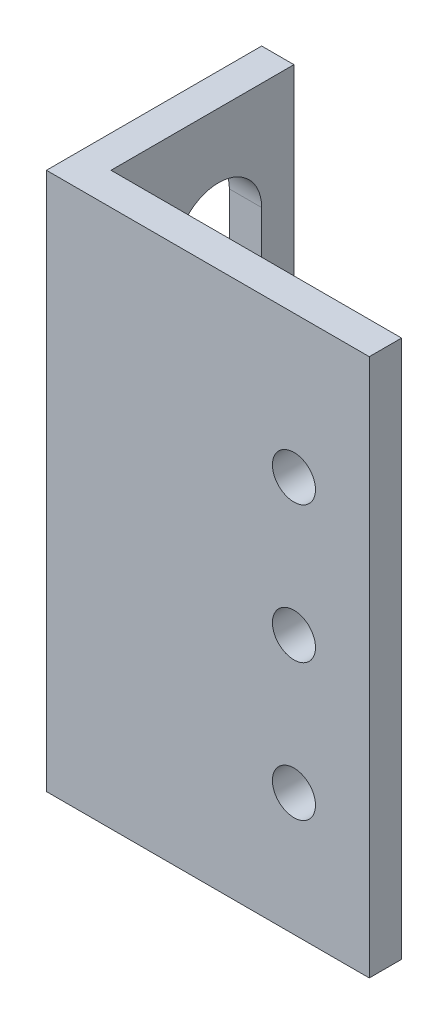
SolidWorks part; units mm, degrees
ref_plane "前视基准面" through (0, 0, 0) normal (0, 0, 1) x (1, 0, 0)
ref_plane "上视基准面" through (0, 0, 0) normal (0, 1, 0) x (1, 0, 0)
ref_plane "右视基准面" through (0, 0, 0) normal (1, 0, 0) x (0, 0, -1)
sketch "草图1" plane through (0, 0, 0) normal (0, 1, 0) x (1, 0, 0)
  line L2 (-1.5, 10) -> (1.5, 10)
  line L3 (-1.5, 10) -> (-1.5, -10)
  line L4 (-1.5, -10) -> (1.5, -10)
  line L5 (1.5, 10) -> (1.5, -10)
  line L6 (-1.5, 10) -> (1.5, -10) construction
  line L7 (-1.5, -10) -> (1.5, 10) construction
  line L8 (-1.5, -10) -> (28.5, -10)
  line L9 (-1.5, -10) -> (-1.5, -7)
  line L10 (-1.5, -7) -> (28.5, -7)
  line L11 (28.5, -10) -> (28.5, -7)
  point P2 (0, 0)
  dimension "D1" = 3
  dimension "D2" = 3
  dimension "D3" = 20
  dimension "D4" = 30
extrude "凸台-拉伸1" add sketch "草图1" along normal blind 50 contours L3 L10 L5 L2 | L10 L3 L4 L5 | L8 L11 L10 L5
sketch "草图2" plane through (0, 0, 10) normal (0, 0, 1) x (1, 0, 0)
  line L0 (21.5, 50) -> (21.5, 0) construction
  line L1 (-1.5, 50) -> (28.5, 50) construction
  line L3 (28.5, 50) -> (28.5, 0) construction
  circle A0 centre (21.5, 36.8) radius 2
  circle A2 centre (21.5, 24.1) radius 2
  circle A3 centre (21.5, 11.4) radius 2
  dimension "D1" = 4
  dimension "D2" = 13.2
  dimension "D4" = 12.7
  dimension "D5" = 7
  dimension "D3" = 3
extrude "切除-拉伸1" cut sketch "草图2" against normal blind 10
sketch "草图3" plane through (-1.5, 0, 0) normal (-1, 0, 0) x (0, 0, 1)
  line L0 (-3, 40) -> (-3, 10) construction
  line L1 (1, 40) -> (1, 10)
  line L2 (-7, 40) -> (-7, 10)
  line L4 (-10, 50) -> (-10, 0) construction
  line L5 (-10, 25) -> (10, 25) construction
  line L6 (10, 50) -> (10, 0) construction
  arc A0 (1, 40) -> (-7, 40) centre (-3, 40) ccw
  arc A1 (-7, 10) -> (1, 10) centre (-3, 10) ccw
  point P3 (-3, 25)
  dimension "D3" = 4
  dimension "D1" = 30
  dimension "D2" = 7
extrude "切除-拉伸2" cut sketch "草图3" against normal blind 10
